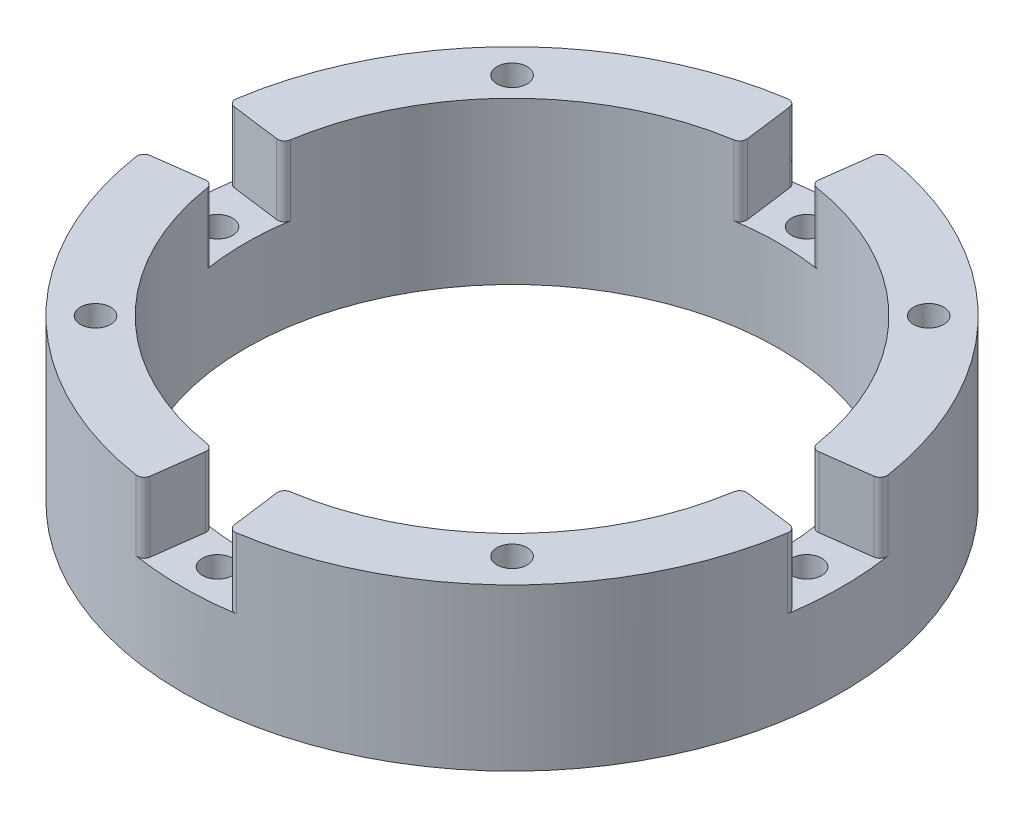
SolidWorks part; units mm, degrees
material "ABS"
ref_plane "Front Plane" through (0, 0, 0) normal (0, 0, 1) x (1, 0, 0)
ref_plane "Top Plane" through (0, 0, 0) normal (0, 1, 0) x (1, 0, 0)
ref_plane "Right Plane" through (0, 0, 0) normal (1, 0, 0) x (0, 0, -1)
sketch "Sketch1" plane through (0, 0, 0) normal (0, 1, 0) x (1, 0, 0)
  line L0 (0, -44.7868) -> (0, 44.7868) construction
  line L1 (-44.2539, 0) -> (44.2539, 0) construction
  circle A0 centre (0, 0) radius 47
  circle A1 centre (0, 0) radius 38
  circle A2 centre (0, 42) radius 2.15
  circle A3 centre (29.6985, 29.6985) radius 2.15
  circle A4 centre (42, 0) radius 2.15
  circle A5 centre (29.6985, -29.6985) radius 2.15
  circle A6 centre (0, -42) radius 2.15
  circle A7 centre (-29.6985, -29.6985) radius 2.15
  circle A8 centre (-42, 0) radius 2.15
  circle A9 centre (-29.6985, 29.6985) radius 2.15
  point P26 (0, 0)
  dimension "D1" = 76
  dimension "D2" = 94
  dimension "D3" = 42
  dimension "D4" = 4.3
  dimension "D5" = 8
extrude "Boss-Extrude1" add sketch "Sketch1" along normal mid plane 23
sketch "Sketch2" plane through (0, 11.5, 0) normal (0, 1, 0) x (1, 0, 0)
  line L0 (0, 0) -> (-6.1347, 46.5979) construction
  line L1 (0, 0) -> (6.1347, 46.5979) construction
  line L2 (0, -44.7868) -> (0, 44.7868) construction
  line L3 (-6.1347, 46.5979) -> (-4.96, 37.6749)
  line L4 (6.1347, 46.5979) -> (4.96, 37.6749)
  circle A0 centre (0, 0) radius 47 construction
  circle A1 centre (0, 0) radius 38 construction
  arc A2 (4.96, 37.6749) -> (-4.96, 37.6749) centre (0, 0) ccw
  arc A3 (6.1347, 46.5979) -> (-6.1347, 46.5979) centre (0, 0) ccw
  dimension "D1" = 7.5
  dimension "D2" = 7.5
extrude "Cut-Extrude1" cut sketch "Sketch2" against normal blind 10
fillet "Fillet1" radius 1 4 edges at (4.96, 6.5, -37.6749) (6.1347, 6.5, -46.5979) (-4.96, 6.5, -37.6749) (-6.1347, 6.5, -46.5979)
pattern_circular "CirPattern1" count 4 over 270 about axis through (0, 0, 0) along (0, 1, 0) of "Cut-Extrude1", "Fillet1"
ref_plane "Plane1" through (0, 0, 0) normal (0, 1, 0) x (1, 0, 0)
